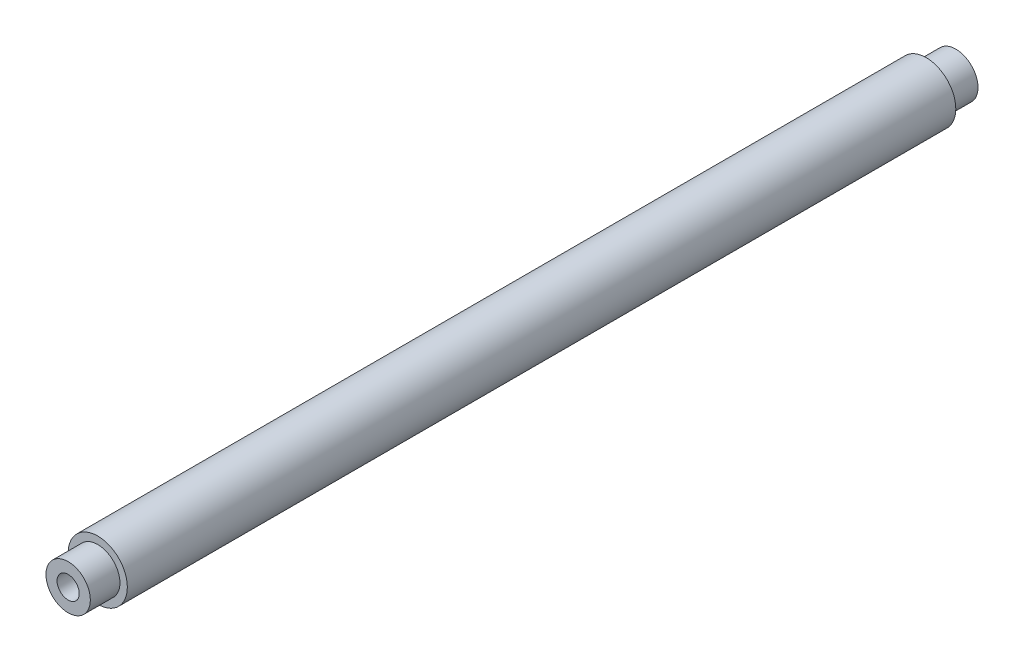
SolidWorks part; units mm, degrees
ref_plane "Plan1" through (0, 0, 0) normal (0, 0, 1) x (1, 0, 0)
ref_plane "Plan2" through (0, 0, 0) normal (0, 1, 0) x (1, 0, 0)
ref_plane "Plan3" through (0, 0, 0) normal (1, 0, 0) x (0, 0, -1)
sketch "Esquisse1" plane through (0, 0, 0) normal (0, 0, 1) x (1, 0, 0)
  circle A0 centre (0, 0) radius 4
  dimension "D1" = 8
extrude "Base-Extrusion" add sketch "Esquisse1" along normal blind 120
sketch "Esquisse2" plane through (0, 0, 0) normal (0, 0, 1) x (1, 0, 0)
  circle A0 centre (0, 0) radius 4 construction
  circle A1 centre (0, 0) radius 3
  circle A2 centre (0, 0) radius 3
  circle A3 centre (0, 0) radius 4
  dimension "D1" = 1
ref_plane "Plan4" through (0, 0, 112) normal (0, 0, 1) x (1, 0, 0)
ref_plane "Plan5" through (0, -4, 0) normal (0, 1, 0) x (-1, 0, 0)
extrude "Enlèv. mat.-Extru.1" cut sketch "Esquisse2" along normal blind 4
sketch "Esquisse3" plane through (0, 0, 120) normal (0, 0, 1) x (1, 0, 0)
  circle A0 centre (0, 0) radius 3 construction
  circle A1 centre (0, 0) radius 4 construction
  circle A2 centre (0, 0) radius 3
  circle A3 centre (0, 0) radius 4
extrude "Enlèv. mat.-Extru.2" cut sketch "Esquisse3" against normal blind 4
hole_wizard "Perçage1" positions "Esquisse5" profile "Esquisse4" legacy
sketch "Esquisse5" plane through (0, 0, 120) normal (0, 0, 1) x (1, 0, 0)
  point P0 (0, 0)
sketch "Esquisse4" plane through (0, 0, 120) normal (1, 0, 0) x (0, -1, 0)
  line L0 (0, 0) -> (0, 11.7511)
  line L1 (0, 11.7511) -> (1.25, 11)
  line L2 (1.25, 11) -> (1.25, 8)
  line L3 (1.25, 8) -> (1.5, 8)
  line L4 (1.5, 0) -> (0, 0)
  line L5 (0, -11.3109) -> (0, 121.1557) construction
  line L6 (0, 11.7511) -> (-1.25, 11) construction
  line L7 (1.5, 8) -> (1.5, 0)
  dimension "Diamètre" = 2.5
  dimension "Profondeur" = 11
  dimension "Diamètre chambrage" = 3
  dimension "Profondeur chambrage" = 8
  dimension "Angle" = 118
hole_wizard "Perçage2" positions "Esquisse7" profile "Esquisse6" legacy
sketch "Esquisse7" plane through (0, 0, 0) normal (0, 0, -1) x (-1, 0, 0)
  point P0 (0, 0)
sketch "Esquisse6" plane through (0, 0, 0) normal (1, 0, 0) x (0, 1, 0)
  line L0 (0, 0) -> (0, 11.7511)
  line L1 (0, 11.7511) -> (1.25, 11)
  line L2 (1.25, 11) -> (1.25, 8)
  line L3 (1.25, 8) -> (1.5, 8)
  line L4 (1.5, 0) -> (0, 0)
  line L5 (0, -11.3109) -> (0, 121.1557) construction
  line L6 (0, 11.7511) -> (-1.25, 11) construction
  line L7 (1.5, 8) -> (1.5, 0)
  dimension "Diamètre" = 2.5
  dimension "Profondeur" = 11
  dimension "Diamètre chambrage" = 3
  dimension "Profondeur chambrage" = 8
  dimension "Angle" = 118
